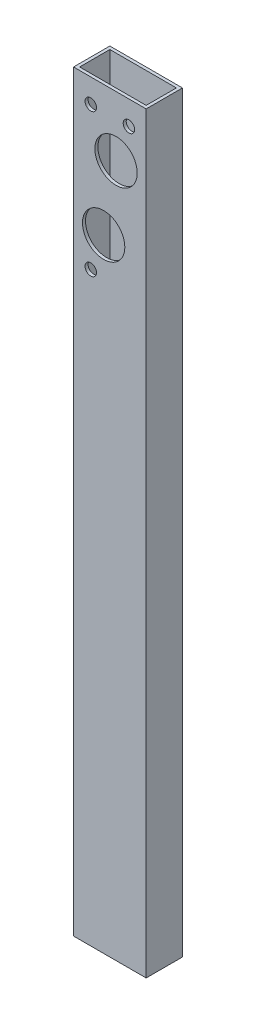
SolidWorks part; units mm, degrees
material "6063-T6"
ref_plane "Front Plane" through (0, 0, 0) normal (0, 0, 1) x (1, 0, 0)
ref_plane "Top Plane" through (0, 0, 0) normal (0, 1, 0) x (1, 0, 0)
ref_plane "Right Plane" through (0, 0, 0) normal (1, 0, 0) x (0, 0, -1)
sketch "Sketch8" plane through (0, 0, 0) normal (0, 0, 1) x (1, 0, 0)
  line L0 (0, 0) -> (0, -50)
  line L1 (0, -50) -> (0, -220)
  line L2 (0, -220) -> (0, -280)
  point P3 (0, 0)
  dimension "D1" = 170
  dimension "D2" = 50
  dimension "D3" = 60
sketch "Sketch1" plane through (0, 0, 0) normal (0, 1, 0) x (1, 0, 0)
  line L1 (-38.1, 19.05) -> (38.1, 19.05)
  line L2 (-38.1, 19.05) -> (-38.1, -19.05)
  line L3 (-38.1, -19.05) -> (38.1, -19.05)
  line L4 (38.1, 19.05) -> (38.1, -19.05)
  line L5 (-38.1, 19.05) -> (38.1, -19.05) construction
  line L6 (-38.1, -19.05) -> (38.1, 19.05) construction
  point P0 (0, 0)
  dimension "D1" = 76.2
  dimension "D2" = 38.1
extrude "Extrude-Thin1" add sketch "Sketch1" along normal blind 510 and the other way up to vertex (280 mm away) thin
sketch "Sketch6" plane through (0, 0, 19.05) normal (0, 0, 1) x (1, 0, 0)
  line L2 (-6.5118, 373.0697) -> (6.5118, 446.9303) construction
  line L3 (-38.1, -280) -> (-38.1, 510) construction
  line L6 (0, -20.955) -> (0, 20.955) construction
  line L7 (-38.1, 510) -> (38.1, 510) construction
  circle A0 centre (6.5118, 446.9303) radius 22.225
  circle A1 centre (-6.5118, 373.0697) radius 22.225
  point P6 (0, 410)
  dimension "D1" = 44.45
  dimension "D2" = 100
  dimension "D4" = 75
  dimension "D5" = 10
extrude "Cut-Extrude1" cut sketch "Sketch6" against normal up to next
hole_wizard "Ø12.0 (12) Diameter Hole2" positions "Sketch9" profile "Sketch10" hole size "Ø12.0" standard "ANSI Metric"
sketch "Sketch9" plane through (0, 0, 19.05) normal (0, 0, 1) x (1, 0, 0)
  line L0 (-20, 485) -> (20, 485)
  line L4 (0, -20.955) -> (0, 20.955) construction
  line L5 (-20, 335) -> (-20, 485)
  line L7 (0, 410) -> (-20, 410)
  line L8 (-6.5118, 373.0697) -> (6.5118, 446.9303) construction
  point P0 (-20, 485)
  point P2 (20, 485)
  point P4 (-20, 335)
  point P23 (0, 485)
  dimension "D1" = 40
  dimension "D2" = 150
sketch "Sketch10" plane through (-20, 485, 19.05) normal (1, 0, 0) x (0, -1, 0)
  line L0 (0, 0) -> (0, 3.175)
  line L1 (0, 3.175) -> (6, 3.175)
  line L2 (6, 3.175) -> (6, 0)
  line L5 (6, 0) -> (0, 0)
  line L11 (0, -6.35) -> (0, 107.95) construction
  dimension "Thru Hole Dia." = 12
  dimension "Thru Hole Depth" = 3.175
hole_wizard "Ø12.0 (12) Diameter Hole1" positions "Sketch2" profile "Sketch3" hole size "Ø12.0" standard "ANSI Metric"
sketch "Sketch2" plane through (0, 0, -19.05) normal (0, 0, -1) x (-1, 0, 0)
  line L1 (-20, -15) -> (20, -15)
  line L2 (-20, -15) -> (-20, -255)
  line L3 (-20, -255) -> (20, -255)
  line L4 (20, -15) -> (20, -255)
  line L5 (0, 20.955) -> (0, -20.955) construction
  point P1 (-20, -15)
  point P2 (20, -255)
  point P69 (-20, -255)
  point P70 (20, -15)
  point P71 (0, -255)
  dimension "D1" = 40
  dimension "D2" = 35
  dimension "D3" = 35
sketch "Sketch3" plane through (20, -15, -19.05) normal (1, 0, 0) x (0, 1, 0)
  line L0 (0, 0) -> (0, 3.175)
  line L1 (0, 3.175) -> (6, 3.175)
  line L2 (6, 3.175) -> (6, 0)
  line L5 (6, 0) -> (0, 0)
  line L11 (0, -6.35) -> (0, 107.95) construction
  dimension "Thru Hole Dia." = 12
  dimension "Thru Hole Depth" = 3.175
sketch "Sketch7" plane through (0, 0, -19.05) normal (0, 0, -1) x (-1, 0, 0)
  line L0 (0, 20.955) -> (0, -20.955) construction
  circle A0 centre (0, -50) radius 22.225
  circle A1 centre (0, -220) radius 22.225
  point P2 (0, -50)
  point P6 (0, -220)
  point P8 (0, 0)
  dimension "D1" = 44.45
extrude "Cut-Extrude2" cut sketch "Sketch7" against normal up to next
